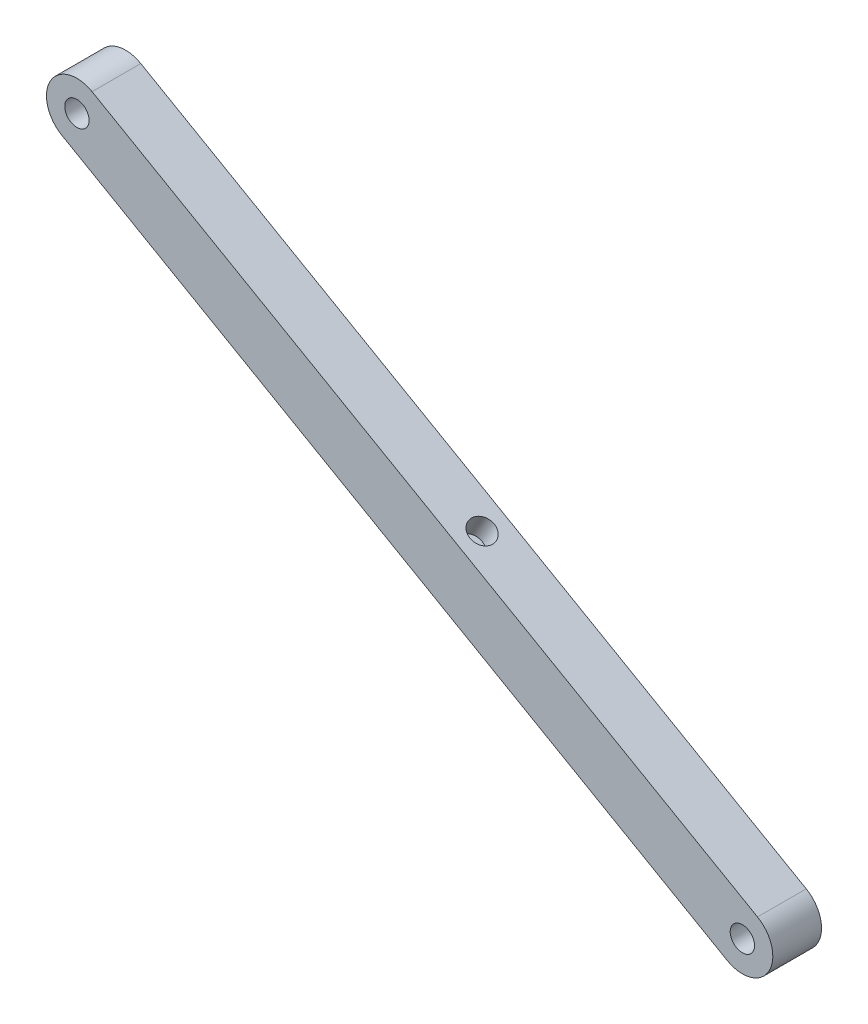
SolidWorks part; units mm, degrees
ref_plane "Спереди" through (0, 0, 0) normal (0, 0, 1) x (1, 0, 0)
ref_plane "Сверху" through (0, 0, 0) normal (0, 1, 0) x (1, 0, 0)
ref_plane "Справа" through (0, 0, 0) normal (1, 0, 0) x (0, 0, -1)
sketch "Sketch1" plane through (0, 0, 0) normal (0, 0, 1) x (1, 0, 0)
  line L0 (-5.265, 31.0446) -> (-59.903, 62.4084) construction
  line L5 (-59.903, 62.4084) -> (-5.265, 31.0446) construction
  line L6 (-58.6584, 64.5765) -> (-4.0204, 33.2128)
  line L7 (-61.1476, 60.2402) -> (-6.5096, 28.8765)
  arc A2 (-58.6584, 64.5765) -> (-61.1476, 60.2402) centre (-59.903, 62.4084) ccw
  arc A3 (-6.5096, 28.8765) -> (-4.0204, 33.2128) centre (-5.265, 31.0446) ccw
  circle A4 centre (-59.903, 62.4084) radius 1
  circle A5 centre (-5.265, 31.0446) radius 1
  point P2 (-32.584, 46.7265)
  dimension "D3" = 2
  dimension "D1" = 63
  dimension "D2" = 5
extrude "Boss-Extrude1" add sketch "Sketch1" along normal blind 4
sketch "Sketch2" plane through (13.3435, 23.2454, 0) normal (0.4978, 0.8673, 0) x (0.8673, -0.4978, 0)
  line L0 (-50.3436, -2) -> (-46.6778, -2) construction
  line L2 (-48.4037, -4) -> (-48.4037, 0) construction
  circle A0 centre (-48.4037, -2) radius 1
  dimension "D1" = 2
extrude "Cut-Extrude1" cut sketch "Sketch2" against normal blind 2
